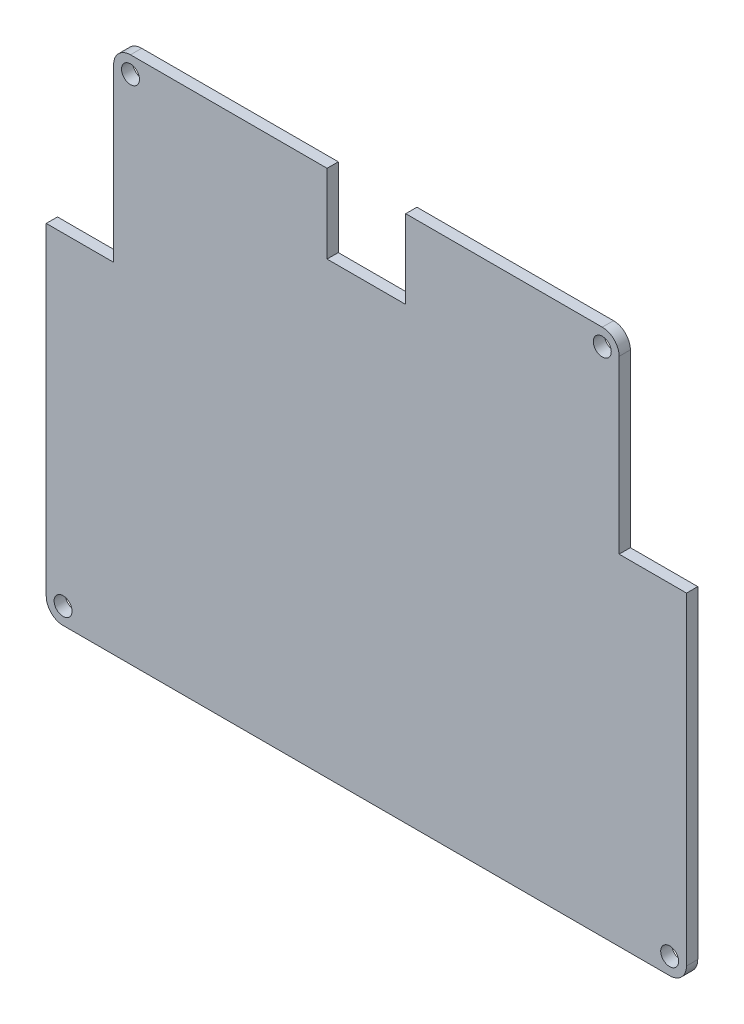
SolidWorks part; units mm, degrees
ref_plane "Front Plane" through (0, 0, 0) normal (0, 0, 1) x (1, 0, 0)
ref_plane "Top Plane" through (0, 0, 0) normal (0, 1, 0) x (1, 0, 0)
ref_plane "Right Plane" through (0, 0, 0) normal (1, 0, 0) x (0, 0, -1)
sketch "Sketch1" plane through (0, 0, 0) normal (0, 0, 1) x (1, 0, 0)
  line L0 (-45, 28.3148) -> (-57, 28.3148)
  line L1 (57, 28.3148) -> (45, 28.3148)
  line L2 (57, 28.3148) -> (57, -29.1852)
  line L3 (54, -32.1852) -> (-54, -32.1852)
  line L4 (-57, 28.3148) -> (-57, -29.1852)
  line L5 (57, 28.3148) -> (-53.0343, -26.3449) construction
  line L6 (53.0343, -26.3449) -> (-57, 28.3148) construction
  line L8 (-45, 28.3148) -> (-45, 58.8148)
  line L9 (-42, 61.8148) -> (-7, 61.8148)
  line L10 (45, 28.3148) -> (45, 58.8148)
  line L11 (-45, 28.3148) -> (43.7091, 61.2804) construction
  line L12 (-43.7091, 61.2804) -> (45, 28.3148) construction
  line L13 (7, 61.8148) -> (42, 61.8148)
  line L15 (-7, 61.8148) -> (-7, 47.8148)
  line L16 (-7, 47.8148) -> (7, 47.8148)
  line L17 (7, 61.8148) -> (7, 47.8148)
  line L18 (-7, 61.8148) -> (7, 47.8148) construction
  line L19 (-7, 47.8148) -> (7, 61.8148) construction
  line L20 (0, -1.1) -> (0, 1.1) construction
  arc A0 (57, -29.1852) -> (54, -32.1852) centre (54, -29.1852) cw
  circle A1 centre (54, -29.1852) radius 1.6
  circle A4 centre (-54, -29.1852) radius 1.6
  arc A5 (-57, -29.1852) -> (-54, -32.1852) centre (-54, -29.1852) ccw
  arc A8 (45, 58.8148) -> (42, 61.8148) centre (42, 58.8148) ccw
  circle A9 centre (42, 58.8148) radius 1.6
  arc A10 (-45, 58.8148) -> (-42, 61.8148) centre (-42, 58.8148) cw
  circle A11 centre (-42, 58.8148) radius 1.6
  point P0 (0, 0)
  point P6 (0, 45.0374)
  point P11 (0, 54.8148)
  dimension "D7" = 3
  dimension "D8" = 3.2
  dimension "D2" = 3
  dimension "D11" = 3.2
  dimension "D3" = 12
  dimension "D4" = 94
  dimension "D5" = 80
  dimension "D6" = 50
  dimension "D9" = 114
  dimension "D10" = 60.5
extrude "Boss-Extrude1" add sketch "Sketch1" along normal blind 2
